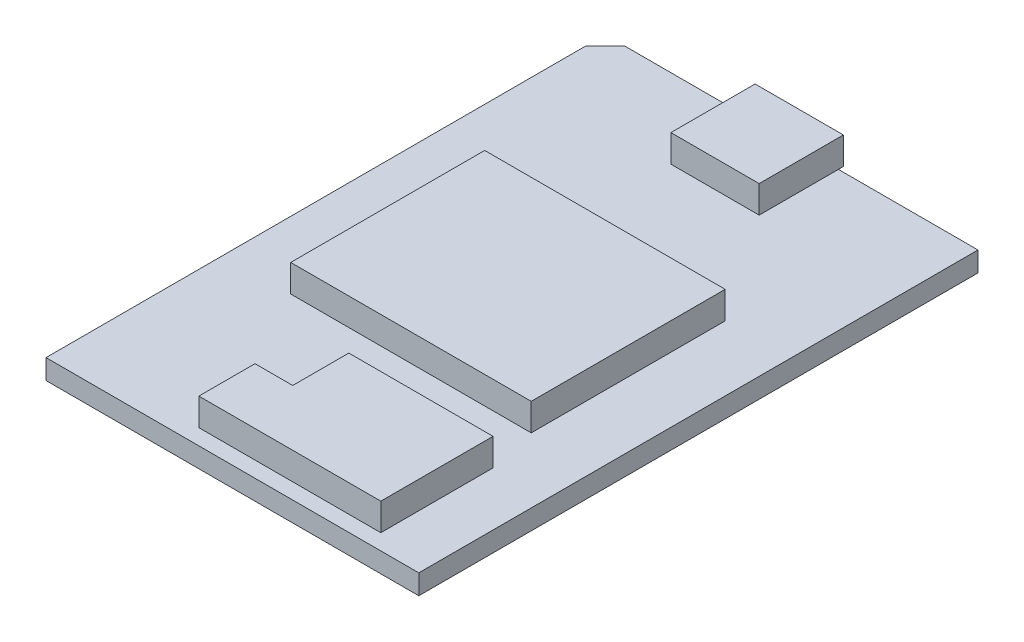
SolidWorks part; units mm, degrees
ref_plane "Front Plane" through (0, 0, 0) normal (0, 0, 1) x (1, 0, 0)
ref_plane "Top Plane" through (0, 0, 0) normal (0, 1, 0) x (1, 0, 0)
ref_plane "Right Plane" through (0, 0, 0) normal (1, 0, 0) x (0, 0, -1)
sketch "Sketch2" plane through (0, 0, 0) normal (0, 1, 0) x (1, 0, 0)
  line L0 (0, 43.4) -> (1.6, 45)
  line L1 (0, 0) -> (30, 0)
  line L2 (0, 0) -> (0, 45)
  line L3 (0, 45) -> (30, 45)
  line L4 (30, 0) -> (30, 45)
  dimension "D1" = 45
  dimension "D2" = 30
  dimension "D3" = 1.6
  dimension "D4" = 1.6
extrude "Boss-Extrude1" add sketch "Sketch2" along normal blind 1.6 contours L1 L4 L3 L0 L2
sketch "Sketch3" plane through (0, 1.6, 0) normal (0, 1, 0) x (1, 0, 0)
  line L1 (5.4143, 29.8867) -> (24.7694, 29.8867)
  line L2 (5.4143, 29.8867) -> (5.4143, 14.2776)
  line L3 (5.4143, 14.2776) -> (24.7694, 14.2776)
  line L4 (24.7694, 29.8867) -> (24.7694, 14.2776)
extrude "Boss-Extrude2" add sketch "Sketch3" along normal blind 2.2
sketch "Sketch4" plane through (0, 1.6, 0) normal (0, 1, 0) x (1, 0, 0)
  line L0 (1.6, 45) -> (30, 45) construction
  line L1 (11.6626, 45) -> (18.7675, 45)
  line L2 (11.6626, 45) -> (11.6626, 38.6226)
  line L3 (11.6626, 38.6226) -> (18.7675, 38.6226)
  line L4 (18.7675, 45) -> (18.7675, 38.6226)
  line L6 (11.6626, 45) -> (18.7675, 45)
  line L7 (11.6626, 45) -> (11.6626, 45.4)
  line L8 (11.6626, 45.4) -> (18.7675, 45.4)
  line L9 (18.7675, 45) -> (18.7675, 45.4)
  line M3 (30, 45) -> (1.6, 45)
  dimension "D1" = 0.4
extrude "Boss-Extrude4" add sketch "Sketch4" along normal blind 2.2 contours L4 L2 L3 M3 | L9 L8 L7 M3
sketch "Sketch5" plane through (0, 0, 0) normal (0, -1, 0) x (-1, 0, 0)
  line L1 (-26.8117, 21.4184) -> (-4.2453, 21.4184)
  line L2 (-26.8117, 21.4184) -> (-26.8117, 8.6026)
  line L3 (-26.8117, 8.6026) -> (-4.2453, 8.6026)
  line L4 (-4.2453, 21.4184) -> (-4.2453, 8.6026)
extrude "Boss-Extrude5" add sketch "Sketch5" along normal blind 1.4
sketch "Sketch6" plane through (0, 0, 0) normal (0, -1, 0) x (-1, 0, 0)
  line L1 (-26.8035, 38.7274) -> (-25.0692, 38.7274)
  line L2 (-26.8035, 38.7274) -> (-26.8035, 36.6606)
  line L3 (-26.8035, 36.6606) -> (-25.0692, 36.6606)
  line L4 (-25.0692, 38.7274) -> (-25.0692, 36.6606)
  line L5 (-26.8035, 34.4694) -> (-25.0692, 34.4694)
  line L6 (-26.8035, 34.4694) -> (-26.8035, 32.3587)
  line L7 (-26.8035, 32.3587) -> (-25.0692, 32.3587)
  line L8 (-25.0692, 34.4694) -> (-25.0692, 32.3587)
  line L9 (-27.5554, 29.6234) -> (-25.5605, 29.6234)
  line L10 (-27.5554, 29.6234) -> (-27.5554, 27.4695)
  line L11 (-27.5554, 27.4695) -> (-25.5605, 27.4695)
  line L12 (-25.5605, 29.6234) -> (-25.5605, 27.4695)
extrude "Boss-Extrude6" add sketch "Sketch6" along normal blind 1.4
sketch "Sketch7" plane through (0, 1.6, 0) normal (0, 1, 0) x (1, 0, 0)
  line L1 (14.0691, 10.2999) -> (25.6751, 10.2999)
  line L2 (14.0691, 10.2999) -> (14.0691, 1.2676)
  line L3 (14.0691, 1.2676) -> (25.6751, 1.2676)
  line L4 (25.6751, 10.2999) -> (25.6751, 1.2676)
  line L5 (14.0691, 5.7837) -> (11.0336, 5.7837)
  line L6 (14.0691, 5.7837) -> (14.0691, 1.2676)
  line L7 (14.0691, 1.2676) -> (11.0336, 1.2676)
  line L8 (11.0336, 5.7837) -> (11.0336, 1.2676)
extrude "Boss-Extrude7" add sketch "Sketch7" along normal blind 2.2 contours L4 L1 L2 L3 | L5 L8 L7 L2
